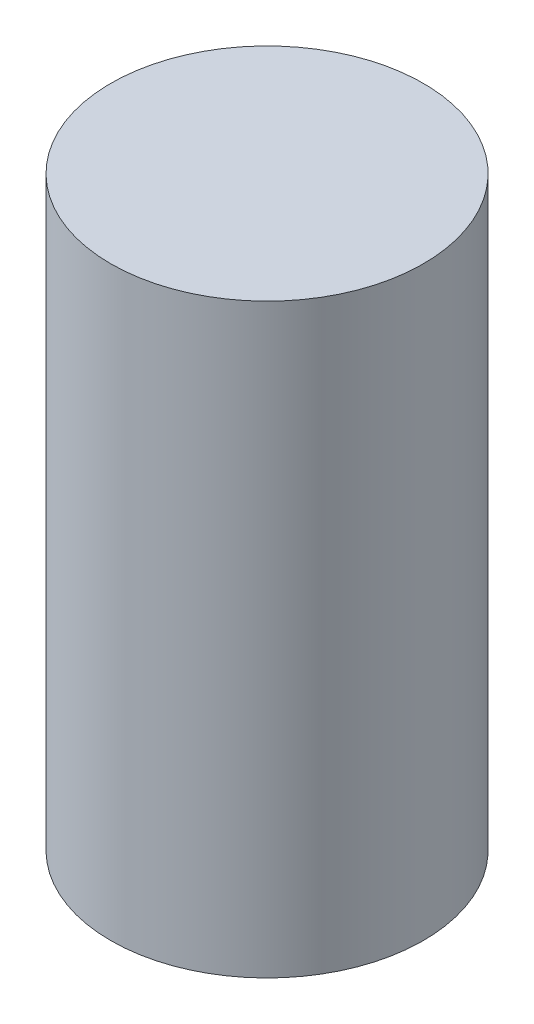
SolidWorks part; units mm, degrees
ref_plane "Plan de face" through (0, 0, 0) normal (0, 0, 1) x (1, 0, 0)
ref_plane "Plan de dessus" through (0, 0, 0) normal (0, 1, 0) x (1, 0, 0)
ref_plane "Plan de droite" through (0, 0, 0) normal (1, 0, 0) x (0, 0, -1)
sketch "Esquisse1" plane through (0, 0, 0) normal (0, 1, 0) x (1, 0, 0)
  circle A0 centre (0, 0) radius 40
extrude "Extrusion1" add sketch "Esquisse1" along normal blind 150
